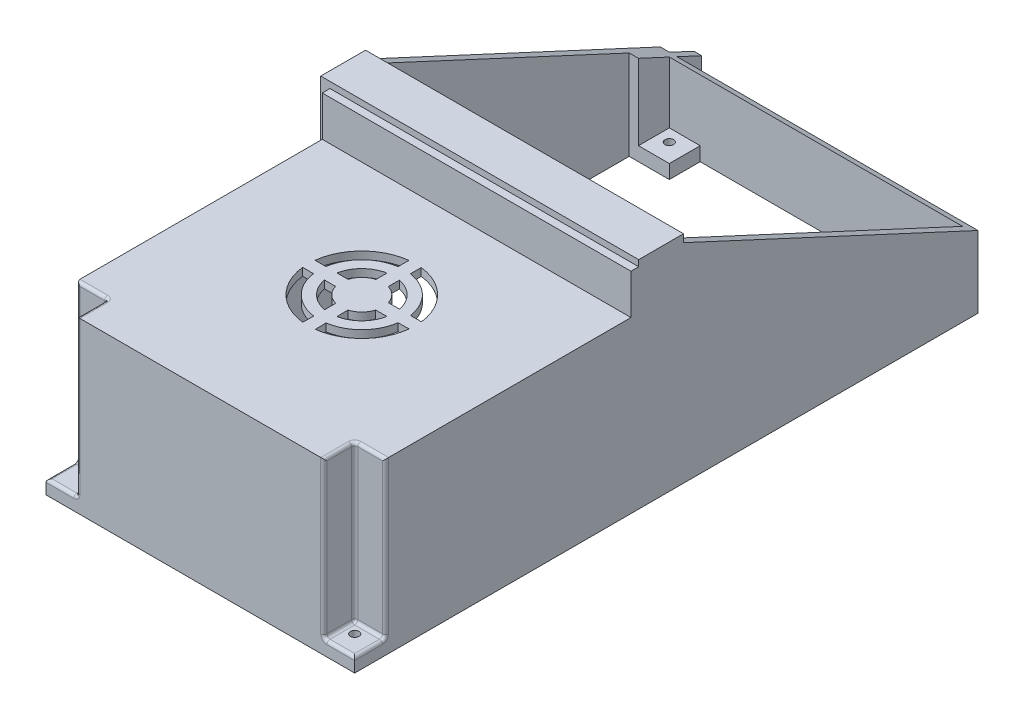
SolidWorks part; units mm, degrees
ref_plane "Front Plane" through (0, 0, 0) normal (0, 0, 1) x (1, 0, 0)
ref_plane "Top Plane" through (0, 0, 0) normal (0, 1, 0) x (1, 0, 0)
ref_plane "Right Plane" through (0, 0, 0) normal (1, 0, 0) x (0, 0, -1)
sketch "Sketch1" plane through (0, 0, 0) normal (0, 1, 0) x (1, 0, 0)
  line L0 (0, 0) -> (100, 0)
  line L1 (100, 0) -> (100, 201.9222)
  line L14 (0, 202) -> (0, 209.9222)
  line L15 (0, 209.9222) -> (2.5, 209.9222)
  line L16 (2.5, 209.9222) -> (2.5, 201.9222)
  line L17 (2.5, 201.9222) -> (97.5, 201.9222)
  line L28 (87.5, 199.4222) -> (12.5, 199.4222)
  line L31 (97.5, 12.5) -> (87.5, 12.5)
  line L32 (87.5, 12.5) -> (87.5, 2.5)
  line L33 (87.5, 2.5) -> (12.5, 2.5)
  line L34 (12.5, 2.5) -> (12.5, 12.5)
  line L35 (12.5, 12.5) -> (2.5, 12.5)
  line L37 (2.5, 189.4222) -> (12.5, 189.4222)
  line L38 (12.5, 189.4222) -> (12.5, 199.4222)
  line L39 (97.5, 201.9222) -> (100, 201.9222)
  line L40 (0, 202) -> (-3, 202)
  line L41 (-3, 202) -> (-3, 92)
  line L42 (-3, 92) -> (0, 92)
  line L43 (0, 92) -> (0, 0)
  line L44 (2.5, 12.5) -> (2.5, 94.5)
  line L45 (2.5, 94.5) -> (-0.5, 94.5)
  line L46 (-0.5, 94.5) -> (-0.5, 189.4222)
  line L47 (-0.5, 189.4222) -> (2.5, 189.4222)
  line L48 (97.5, 12.5) -> (97.5, 189.4222)
  line L49 (87.5, 199.4222) -> (87.5, 189.4222)
  line L50 (87.5, 189.4222) -> (97.5, 189.4222)
  dimension "D1" = 100
  dimension "D2" = 202
  dimension "D3" = 3
  dimension "D4" = 10
  dimension "D5" = 10
  dimension "D6" = 2.5
  dimension "D9" = 2.5
  dimension "D10" = 2.5
  dimension "D12" = 10
  dimension "D13" = 2.5
  dimension "D14" = 8
  dimension "D19" = 2.5
  dimension "D21" = 10
  dimension "D22" = 2.5
  dimension "D23" = 10
  dimension "D24" = 110
  dimension "D25" = 10
  dimension "D26" = 10
  dimension "D27" = 10
extrude "Boss-Extrude1" add sketch "Sketch1" along normal blind 67.5
sketch "Sketch2" plane through (0, 0, 0) normal (1, 0, 0) x (0, 0, -1)
  line L0 (209.9222, 0) -> (209.9222, 19.5)
  line L1 (209.9222, 67.5) -> (209.9222, 0) construction
  line L2 (209.9222, 19.5) -> (106.5201, 67.5)
  line L3 (0, 67.5) -> (201.9222, 67.5) construction
  line L4 (106.5201, 67.5) -> (209.9222, 67.5)
  line L5 (209.9222, 67.5) -> (209.9222, 19.5)
  dimension "D1" = 19.5
  dimension "D2" = 114
extrude "Cut-Extrude1" cut sketch "Sketch2" along normal through all and the other way through all contours L2 L4 L5
sketch "Sketch3" plane through (0, 67.5, 0) normal (0, 1, 0) x (1, 0, 0)
  line L1 (0, 0) -> (10, 0)
  line L2 (0, 0) -> (0, 10)
  line L3 (0, 10) -> (10, 10)
  line L4 (10, 0) -> (10, 10)
  line L5 (100, 0) -> (90, 0)
  line L6 (100, 0) -> (100, 10)
  line L7 (100, 10) -> (90, 10)
  line L8 (90, 0) -> (90, 10)
  line L9 (97.5, 199.4222) -> (87.5, 199.4222)
  line L10 (97.5, 199.4222) -> (97.5, 189.4222)
  line L11 (97.5, 189.4222) -> (87.5, 189.4222)
  line L12 (87.5, 199.4222) -> (87.5, 189.4222)
  line L17 (12.5, 189.4222) -> (2.5, 189.4222)
  line L18 (12.5, 189.4222) -> (12.5, 199.4222)
  line L19 (12.5, 199.4222) -> (2.5, 199.4222)
  line L20 (2.5, 189.4222) -> (2.5, 199.4222)
  dimension "D1" = 10
  dimension "D2" = 10
  dimension "D3" = 10
  dimension "D4" = 10
  dimension "D5" = 10
  dimension "D6" = 10
  dimension "D7" = 10
  dimension "D8" = 10
extrude "Cut-Extrude2" cut sketch "Sketch3" against normal blind 63
sketch "Sketch4" plane through (0, 0, 0) normal (1, 0, 0) x (0, 0, -1)
  line L0 (106.5201, 67.5) -> (210, 15)
  line L1 (210, 15) -> (210, 67.5)
  line L2 (210, 67.5) -> (106.5201, 67.5)
sketch "Sketch13" plane through (0, 67.5, 0) normal (0, 1, 0) x (1, 0, 0)
  line L1 (-3, 92) -> (102.4447, 92)
  line L2 (-3, 92) -> (-3, -2.7446)
  line L3 (-3, -2.7446) -> (102.4447, -2.7446)
  line L4 (102.4447, 92) -> (102.4447, -2.7446)
extrude "Cut-Extrude7" cut sketch "Sketch13" against normal blind 15
sketch "Sketch7" plane through (0, 4.5, 0) normal (0, 1, 0) x (1, 0, 0)
  line L1 (0, 0) -> (10, 0) construction
  line L2 (100, 201.9222) -> (100, 106.5201) construction
  line L4 (90, 0) -> (100, 0) construction
  line L5 (100, 0) -> (100, 10) construction
  line L8 (2.5, 201.9222) -> (100, 201.9222) construction
  line L9 (2.5, 201.9222) -> (100, 201.9222) construction
  line L10 (0, 106.5201) -> (0, 210) construction
  circle A0 centre (6.5, 6.5) radius 1.4
  circle A1 centre (93.5, 6.5) radius 1.4
  circle A2 centre (93.5, 195.4222) radius 1.4
  circle A3 centre (6.5, 195.4222) radius 1.4
  dimension "D9" = 2.8
  dimension "D10" = 2.8
  dimension "D11" = 2.8
  dimension "D12" = 2.8
  dimension "D2" = 6.5
  dimension "D3" = 6.5
  dimension "D4" = 6.5
  dimension "D5" = 6.5
  dimension "D6" = 6.5
  dimension "D7" = 6.5
  dimension "D8" = 6.5
extrude "Cut-Extrude3" cut sketch "Sketch7" against normal blind 2.5
sketch "Sketch6" plane through (0, 52.5, 0) normal (0, 1, 0) x (1, 0, 0)
  line L3 (0, 10) -> (10, 10)
  line L4 (10, 10) -> (10, 0)
  line L5 (10, 0) -> (90, 0)
  line L6 (90, 0) -> (90, 10)
  line L7 (90, 10) -> (100, 10)
  line L8 (100, 10) -> (100, 92)
  line L10 (0, 92) -> (0, 10)
  line L11 (0, 92) -> (100, 92)
extrude "Boss-Extrude3" add sketch "Sketch6" along normal blind 2.5
fillet "Fillet1" radius 1 18 edges at (5, 4.5, 0) (95, 4.5, 0) (100, 4.5, -5) (10, 4.5, -5) (10, 29.75, 0) (5, 4.5, -10) (10, 29.75, -10) (90, 4.5, -5) (90, 29.75, 0) (95, 4.5, -10) (90, 29.75, -10) (100, 29.75, -10) (95, 55, -10) (90, 55, -5) (10, 55, -5) (5, 55, -10) (0, 4.5, -5) (0, 29.75, -10)
sketch "Sketch8" plane through (0, 55, 0) normal (0, 1, 0) x (1, 0, 0)
  line L0 (1, 103.6008) -> (99, 1) construction
  line L1 (99, 103.6008) -> (1, 1) construction
  line L3 (48, 69.6754) -> (52, 69.6754)
  line L4 (48, 69.6754) -> (48, 54.3943)
  line L5 (48, 54.3943) -> (32.1114, 54.3943)
  line L6 (32.1114, 54.3943) -> (32.1114, 50.3943)
  line L7 (32.1114, 50.3943) -> (48.1794, 50.3943)
  line L8 (48.1794, 50.3943) -> (48.1794, 34.4652)
  line L9 (48.1794, 34.4652) -> (52.1794, 34.4652)
  line L10 (52.1794, 34.4652) -> (52.0058, 50.2004)
  line L11 (52.0058, 50.2004) -> (67.9736, 50.3766)
  line L12 (67.9736, 50.3766) -> (67.9736, 54.3766)
  line L13 (67.9736, 54.3766) -> (51.9831, 54.3766)
  line L14 (51.9831, 54.3766) -> (52, 69.6754)
  circle A0 centre (50, 52.3004) radius 17.375
  circle A1 centre (50, 52.3004) radius 13.875
  circle A2 centre (50, 52.3004) radius 10.375
  circle A3 centre (50, 52.3004) radius 6.875
  point P17 (50, 69.6754)
  dimension "D1" = 34.75
  dimension "D2" = 27.75
  dimension "D3" = 20.75
  dimension "D4" = 13.75
  dimension "D5" = 4
  dimension "D6" = 4
  dimension "D7" = 4
  dimension "D8" = 4
extrude "Cut-Extrude4" cut sketch "Sketch8" against normal blind 2.5 contours A1 L4 A0 L5 | A1 L13 A0 L14 | A1 L10 A0 L11 | A1 L7 A0 L8 | A3 L7 A2 L8 | A3 L4 A2 L5 | A3 L13 A2 L14 | A3 L10 A2 L11
sketch "Sketch9" plane through (0, 52.5, 0) normal (0, -1, 0) x (1, 0, 0)
  line L0 (37.7445, -39.984) -> (62.2588, -64.6135)
  circle A1 centre (65.9624, -68.3345) radius 3
  arc A2 (48.1794, -35.021) -> (32.7299, -50.3943) centre (50, -52.3004) ccw construction
  arc A3 (51.9999, -69.5599) -> (67.2505, -54.3766) centre (50, -52.3004) ccw construction
  circle A4 centre (34.0408, -36.263) radius 3
  circle A5 centre (34.0408, -36.263) radius 1.4
  circle A6 centre (65.9624, -68.3345) radius 1.4
  point P12 (50.0016, -52.2988)
  dimension "D3" = 6
  dimension "D4" = 6
  dimension "D5" = 2.8
  dimension "D6" = 2.8
  dimension "D1" = 22.625
  dimension "D2" = 22.625
extrude "Boss-Extrude4" add sketch "Sketch9" along normal blind 4 contours A4 A5 | A1 A6
sketch "Sketch12" plane through (0, 55, 0) normal (0, 1, 0) x (1, 0, 0)
  line L1 (100, 104.6008) -> (-2.9127, 104.6008)
  line L2 (100, 104.6008) -> (100, -1.936)
  line L3 (100, -1.936) -> (-2.9127, -1.936)
  line L4 (-2.9127, 104.6008) -> (-2.9127, -1.936)
sketch "Sketch14" plane through (0, 67.5, 0) normal (0, 1, 0) x (1, 0, 0)
  line L1 (-3, 92) -> (100, 92)
  line L2 (-3, 92) -> (-3, 106.5201)
  line L3 (-3, 106.5201) -> (100, 106.5201)
  line L4 (100, 92) -> (100, 106.5201)
extrude "Boss-Extrude5" add sketch "Sketch14" along normal blind 2.5
sketch "Sketch15" plane through (0, 0, -92) normal (0, 0, 1) x (1, 0, 0)
  line L0 (100, 55) -> (-2.9127, 55) construction
  line L1 (0, 68) -> (100, 68)
  line L2 (0, 68) -> (0, 55)
  line L3 (0, 55) -> (100, 55)
  line L4 (100, 68) -> (100, 55)
  line L5 (0, 15) -> (0, 67.5) construction
extrude "Boss-Extrude6" add sketch "Sketch15" along normal blind 2.5
